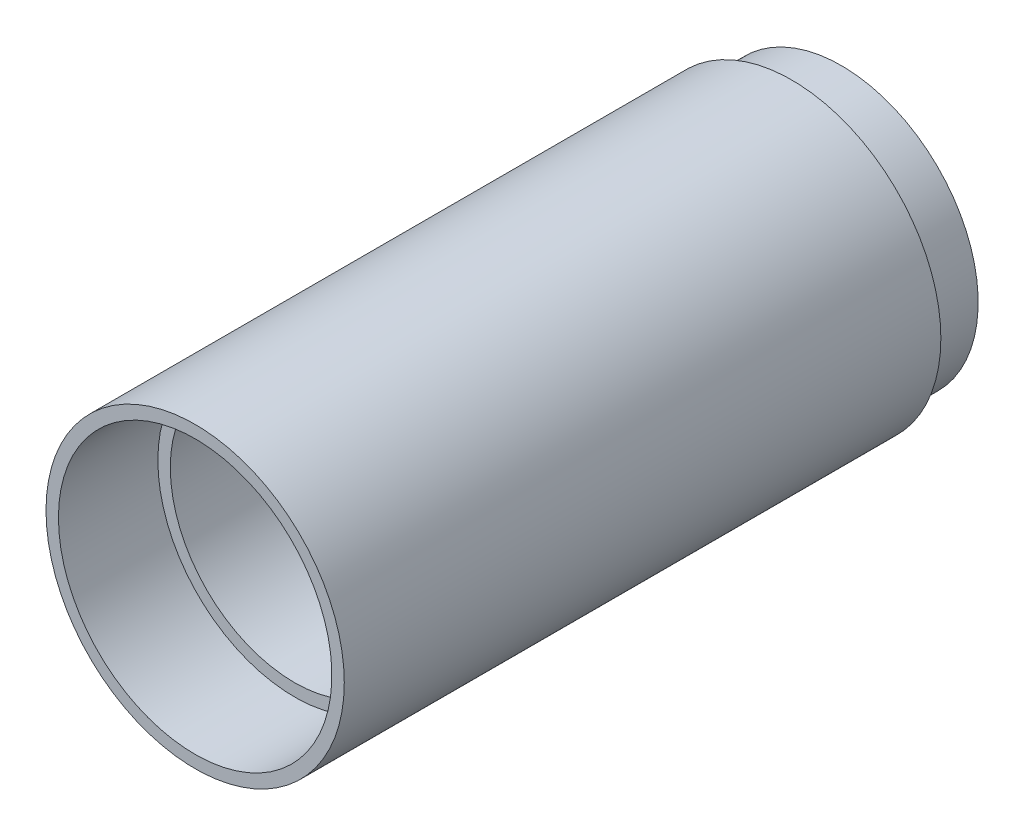
SolidWorks part; units mm, degrees
ref_plane "前视基准面" through (0, 0, 0) normal (0, 0, 1) x (1, 0, 0)
ref_plane "上视基准面" through (0, 0, 0) normal (0, 1, 0) x (1, 0, 0)
ref_plane "右视基准面" through (0, 0, 0) normal (1, 0, 0) x (0, 0, -1)
sketch "草图2" plane through (0, 0, 0) normal (0, 0, 1) x (1, 0, 0)
  circle A0 centre (-112.6061, 79.5679) radius 60
  dimension "D1" = 120
extrude "凸台-拉伸1" add sketch "草图2" along normal blind 200
sketch "草图3" plane through (0, 0, 0) normal (0, 0, -1) x (-1, 0, 0)
  circle A2 centre (112.6061, 79.5679) radius 50
  circle A3 centre (112.6061, 79.5679) radius 50
  dimension "D1" = 10
extrude "切除-拉伸1" cut sketch "草图3" against normal blind 200
sketch "草图4" plane through (0, 0, 0) normal (0, 0, -1) x (-1, 0, 0)
  circle A1 centre (112.6061, 79.5679) radius 50
  circle A2 centre (112.6061, 79.5679) radius 55
  circle A3 centre (112.6061, 79.5679) radius 55
  dimension "D1" = 5
extrude "凸台-拉伸2" add sketch "草图4" along normal blind 20
sketch "草图5" plane through (0, 0, 200) normal (0, 0, 1) x (1, 0, 0)
  circle A0 centre (-112.6061, 79.5679) radius 55
  circle A1 centre (-112.6061, 79.5679) radius 60
  circle A2 centre (-112.6061, 79.5679) radius 60
  dimension "D1" = 0
  dimension "D2" = 5
extrude "凸台-拉伸3" add sketch "草图5" along normal up to surface (40 mm away)
